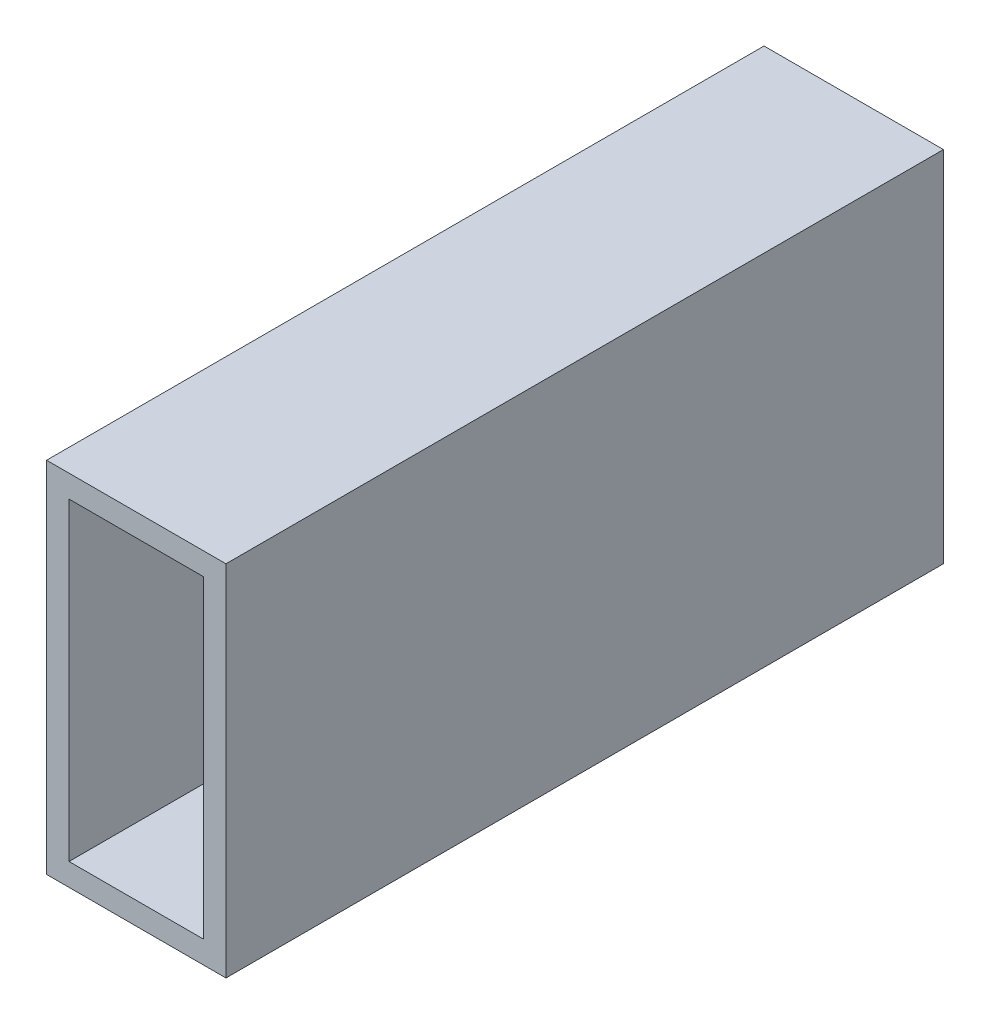
SolidWorks part; units mm, degrees
ref_plane "Front Plane" through (0, 0, 0) normal (0, 0, 1) x (1, 0, 0)
ref_plane "Top Plane" through (0, 0, 0) normal (0, 1, 0) x (1, 0, 0)
ref_plane "Right Plane" through (0, 0, 0) normal (1, 0, 0) x (0, 0, -1)
sketch "Sketch1" plane through (0, 0, 0) normal (0, 0, 1) x (1, 0, 0)
  line L0 (-9.525, 22.225) -> (9.525, 22.225)
  line L1 (-12.7, 25.4) -> (12.7, 25.4)
  line L2 (-12.7, 25.4) -> (-12.7, -25.4)
  line L3 (-12.7, -25.4) -> (12.7, -25.4)
  line L4 (12.7, 25.4) -> (12.7, -25.4)
  line L5 (-12.7, 25.4) -> (12.7, -25.4) construction
  line L6 (-12.7, -25.4) -> (12.7, 25.4) construction
  line L7 (9.525, 22.225) -> (9.525, -22.225)
  line L8 (-9.525, -22.225) -> (9.525, -22.225)
  line L9 (-9.525, 22.225) -> (-9.525, -22.225)
  point P0 (0, 0)
  dimension "D1" = 25.4
  dimension "D2" = 50.8
  dimension "D3" = 3.175
extrude "Boss-Extrude1" add sketch "Sketch1" along normal mid plane 101.6
